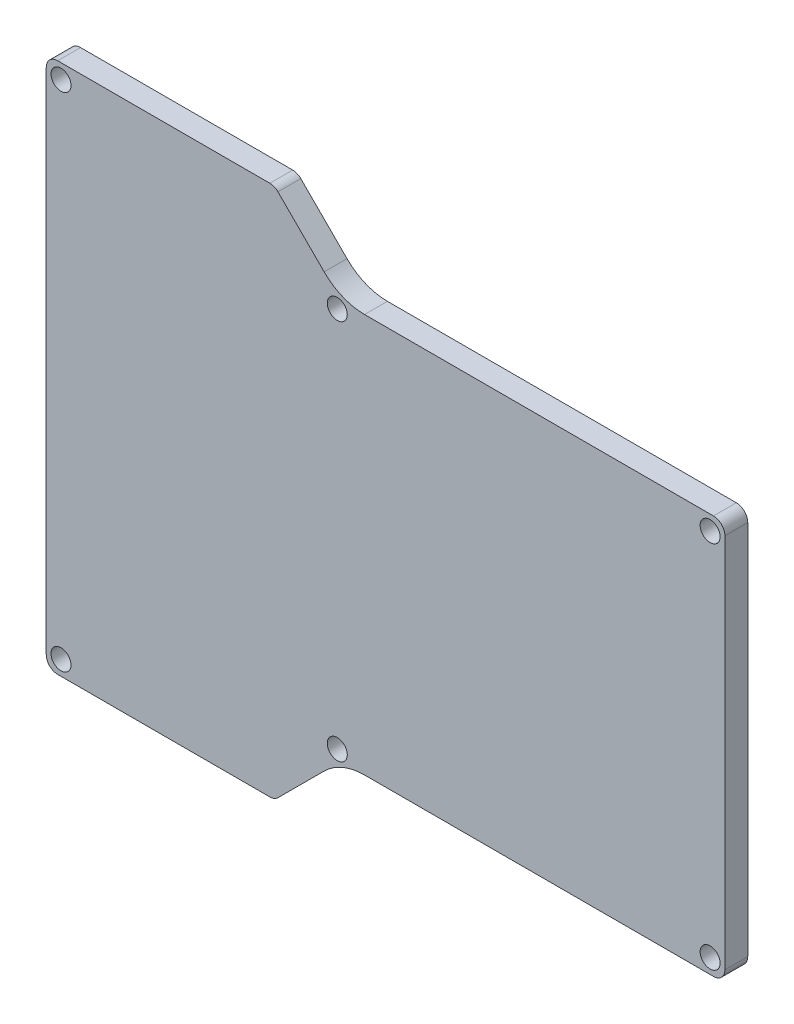
SolidWorks part; units mm, degrees
ref_plane "Front Plane" through (0, 0, 0) normal (0, 0, 1) x (1, 0, 0)
ref_plane "Top Plane" through (0, 0, 0) normal (0, 1, 0) x (1, 0, 0)
ref_plane "Right Plane" through (0, 0, 0) normal (1, 0, 0) x (0, 0, -1)
sketch "Sketch1" plane through (0, 0, 0) normal (0, 0, 1) x (1, 0, 0)
  line L0 (22.2426, -103.6838) -> (30.3379, -95.5885) construction
  line L3 (97.3873, -22.8746) -> (37.404, -22.8746) construction
  line L4 (30.3329, -19.9457) -> (22.2426, -11.8554) construction
  line L5 (20.8284, -11.2696) -> (-16.3, -11.2696) construction
  line L6 (-18.3, -13.2696) -> (-18.3, -29.9684) construction
  line L7 (-18.3, -33.5708) -> (-18.3, -55.9684) construction
  line L8 (-18.3, -59.5708) -> (-18.3, -81.9684) construction
  line L9 (-18.3, -85.5708) -> (-18.3, -102.2696) construction
  line L10 (-16.3, -104.2696) -> (20.8284, -104.2696) construction
  line L11 (22.2426, -103.6838) -> (30.3379, -95.5885)
  line L13 (37.409, -92.6596) -> (97.3869, -92.6596) construction
  line L14 (97.3873, -22.8746) -> (37.404, -22.8746)
  line L15 (30.3329, -19.9457) -> (22.2426, -11.8554)
  line L16 (20.8284, -11.2696) -> (-16.3, -11.2696)
  line L17 (-18.3, -13.2696) -> (-18.3, -29.9684)
  line L18 (-18.3, -33.5708) -> (-18.3, -55.9684)
  line L19 (-18.3, -59.5708) -> (-18.3, -81.9684)
  line L20 (-18.3, -85.5708) -> (-18.3, -102.2696)
  line L21 (-16.3, -104.2696) -> (20.8284, -104.2696)
  line L23 (97.3869, -92.6596) -> (98.455, -92.6596)
  line L24 (100.455, -90.503) -> (100.455, -102.2696) construction
  line L25 (37.409, -92.6596) -> (97.3869, -92.6596)
  line L26 (100.455, -90.6596) -> (100.455, -24.8746)
  line L27 (100.455, -13.2696) -> (100.455, -25.0311) construction
  line L28 (98.455, -22.8746) -> (97.3873, -22.8746)
  circle A0 centre (-15.7166, -13.853) radius 1.25 construction
  circle A1 centre (32.6226, -24.4179) radius 1.25 construction
  circle A2 centre (97.8692, -25.4604) radius 1.25 construction
  circle A3 centre (97.8692, -90.0738) radius 1.25 construction
  circle A4 centre (32.6276, -91.1163) radius 1.25 construction
  circle A5 centre (-15.7166, -101.6862) radius 1.25 construction
  arc A6 (37.409, -92.6596) -> (30.3379, -95.5885) centre (37.409, -102.6596) ccw construction
  arc A9 (30.3329, -19.9457) -> (37.404, -22.8746) centre (37.404, -12.8746) ccw construction
  arc A10 (22.2426, -11.8554) -> (20.8284, -11.2696) centre (20.8284, -13.2696) ccw construction
  arc A11 (-16.3, -11.2696) -> (-18.3, -13.2696) centre (-16.3, -13.2696) ccw construction
  arc A12 (-18.3, -102.2696) -> (-16.3, -104.2696) centre (-16.3, -102.2696) ccw construction
  circle A13 centre (-15.7166, -13.853) radius 1.25 construction
  circle A14 centre (32.6226, -24.4179) radius 1.25 construction
  circle A15 centre (97.8692, -25.4604) radius 1.25 construction
  circle A16 centre (97.8692, -90.0738) radius 1.25 construction
  circle A17 centre (32.6276, -91.1163) radius 1.25 construction
  circle A18 centre (-15.7166, -101.6862) radius 1.25 construction
  arc A19 (37.409, -92.6596) -> (30.3379, -95.5885) centre (37.409, -102.6596) ccw
  arc A20 (98.455, -92.6596) -> (100.455, -90.6596) centre (98.455, -90.6596) ccw
  arc A21 (100.455, -24.8746) -> (98.455, -22.8746) centre (98.455, -24.8746) ccw
  arc A22 (30.3329, -19.9457) -> (37.404, -22.8746) centre (37.404, -12.8746) ccw
  arc A23 (22.2426, -11.8554) -> (20.8284, -11.2696) centre (20.8284, -13.2696) ccw
  arc A24 (-16.3, -11.2696) -> (-18.3, -13.2696) centre (-16.3, -13.2696) ccw
  arc A25 (-18.3, -102.2696) -> (-16.3, -104.2696) centre (-16.3, -102.2696) ccw
  circle A26 centre (-15.7166, -101.6862) radius 1.75
  circle A27 centre (-15.7166, -13.853) radius 1.75
  circle A28 centre (32.6226, -24.4179) radius 1.75
  circle A29 centre (32.6276, -91.1163) radius 1.75
  circle A30 centre (97.8692, -90.0738) radius 1.75
  circle A31 centre (97.8692, -25.4604) radius 1.75
  arc A32 (20.8284, -104.2696) -> (22.2426, -103.6838) centre (20.8284, -102.2696) ccw construction
  arc A33 (20.8284, -104.2696) -> (22.2426, -103.6838) centre (20.8284, -102.2696) ccw
  spline S0 degree 3 poles (2976.4276, 112.2479) (-37.7428, 62.4762) (-18.2968, 15.3618) (-18.2968, -31.7696) (-18.2968, -78.9007) (-37.7426, -126.0148) (2976.3751, -175.7863) knots -0.139593 -0.139593 -0.139593 -0.139593 0.001801 0.001801 0.001801 0.143195 0.143195 0.143195 0.143195 only from (-18.3, -29.9684) to (-18.3, -33.5708) construction
  spline S1 degree 3 poles (2976.4276, 86.2479) (-37.7428, 36.4762) (-18.2968, -10.6382) (-18.2968, -57.7696) (-18.2968, -104.9007) (-37.7426, -152.0148) (2976.3751, -201.7863) knots -0.139593 -0.139593 -0.139593 -0.139593 0.001801 0.001801 0.001801 0.143195 0.143195 0.143195 0.143195 only from (-18.3, -55.9684) to (-18.3, -59.5708) construction
  spline S2 degree 3 poles (2976.4276, 60.2479) (-37.7428, 10.4762) (-18.2968, -36.6382) (-18.2968, -83.7696) (-18.2968, -130.9007) (-37.7426, -178.0148) (2976.3751, -227.7863) knots -0.139593 -0.139593 -0.139593 -0.139593 0.001801 0.001801 0.001801 0.143195 0.143195 0.143195 0.143195 only from (-18.3, -81.9684) to (-18.3, -85.5708) construction
  spline S3 degree 3 poles (-18.3, -29.9684) (-18.3, -30.5688) (-18.2968, -31.1692) (-18.2968, -31.7696) (-18.2968, -32.37) (-18.3, -32.9704) (-18.3, -33.5708) knots 0 0 0 0 0.001801 0.001801 0.001801 0.003602 0.003602 0.003602 0.003602
  spline S4 degree 3 poles (-18.3, -55.9684) (-18.3, -56.5688) (-18.2968, -57.1692) (-18.2968, -57.7696) (-18.2968, -58.37) (-18.3, -58.9704) (-18.3, -59.5708) knots 0 0 0 0 0.001801 0.001801 0.001801 0.003602 0.003602 0.003602 0.003602
  spline S5 degree 3 poles (-18.3, -81.9684) (-18.3, -82.5688) (-18.2968, -83.1692) (-18.2968, -83.7696) (-18.2968, -84.37) (-18.3, -84.9704) (-18.3, -85.5708) knots 0 0 0 0 0.001801 0.001801 0.001801 0.003602 0.003602 0.003602 0.003602
  point P64 (100.455, -92.6596)
  point P67 (100.455, -22.8746)
  dimension "D2" = 2
  dimension "D1" = 0.5
extrude "Boss-Extrude1" add sketch "Sketch1" along normal blind 4
sketch "Sketch2" plane through (0, 0, 0) normal (0, 0, -1) x (-1, 0, 0)
  line L0 (-77.2763, -44.8746) -> (-9.7841, -44.8746) construction
  line L1 (-77.2763, -68.9796) -> (-71.1434, -68.9796)
  line L2 (-77.2763, -68.9796) -> (-77.2763, -44.8746)
  line L3 (-77.2763, -44.8746) -> (-71.1434, -44.8746)
  line L4 (-71.1434, -68.9796) -> (-71.1434, -44.8746)
  line L5 (-80.2763, -71.9796) -> (-80.2763, -41.8746)
  line L6 (-80.2763, -41.8746) -> (-68.1434, -41.8746)
  line L7 (-68.1434, -71.9796) -> (-68.1434, -41.8746)
  line L8 (-80.2763, -71.9796) -> (-68.1434, -71.9796)
  dimension "D1" = 3
extrude "Cut-Extrude2" cut sketch "Sketch2" against normal blind 1 contours L5 L6 L7 L8
